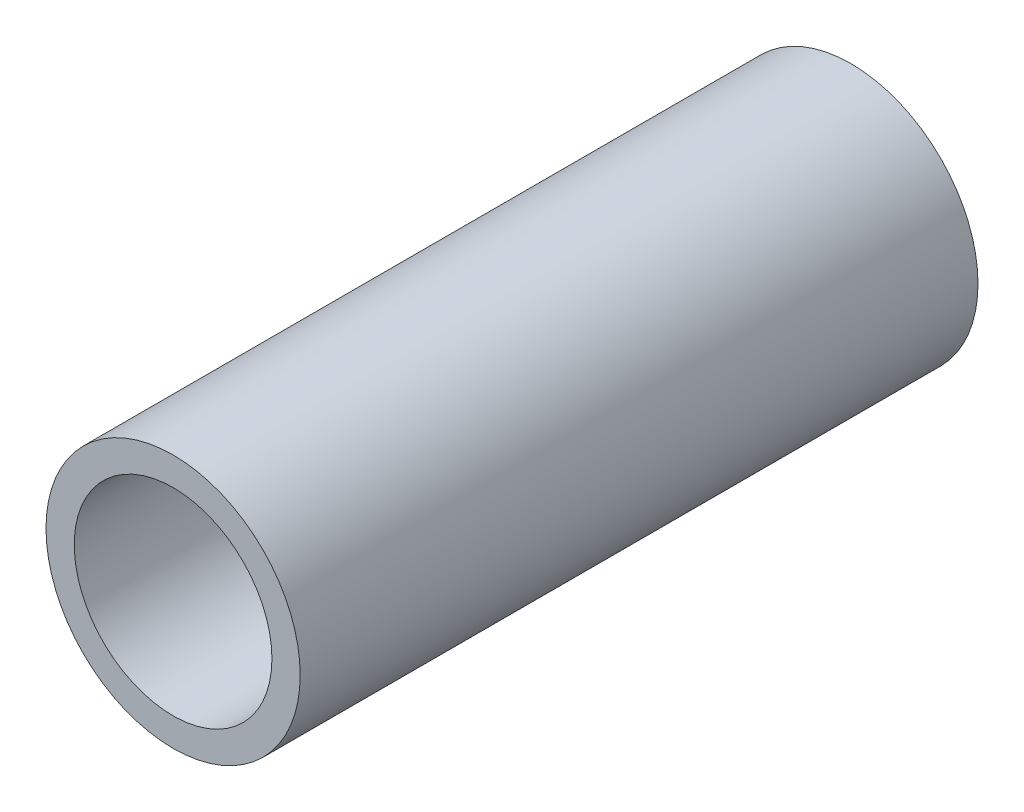
SolidWorks part; units mm, degrees
ref_plane "Front Plane" through (0, 0, 0) normal (0, 0, 1) x (1, 0, 0)
ref_plane "Top Plane" through (0, 0, 0) normal (0, 1, 0) x (1, 0, 0)
ref_plane "Right Plane" through (0, 0, 0) normal (1, 0, 0) x (0, 0, -1)
sketch "Sketch1" plane through (0, 0, 0) normal (0, 0, 1) x (1, 0, 0)
  circle A0 centre (0, 0) radius 9
  circle A1 centre (0, 0) radius 7
  dimension "D1" = 18
  dimension "D2" = 14
extrude "Boss-Extrude1" add sketch "Sketch1" along normal blind 48
